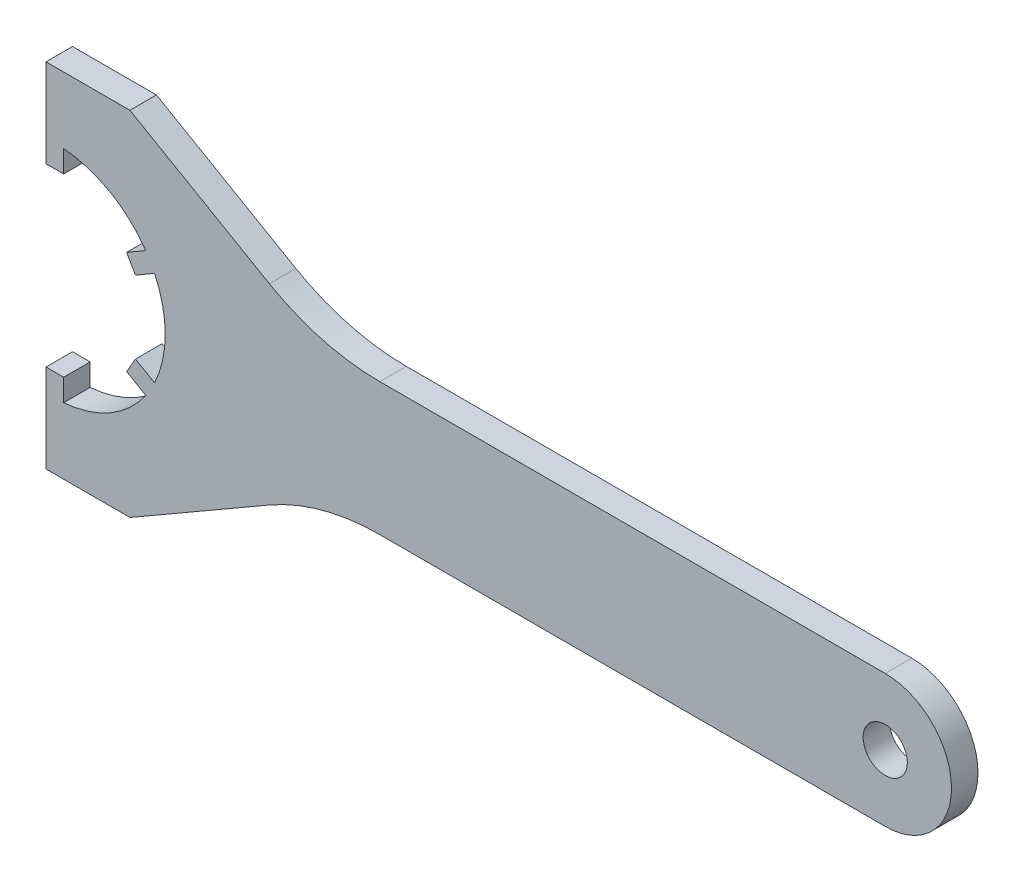
SolidWorks part; units mm, degrees
ref_plane "Front Plane" through (0, 0, 0) normal (0, 0, 1) x (1, 0, 0)
ref_plane "Top Plane" through (0, 0, 0) normal (0, 1, 0) x (1, 0, 0)
ref_plane "Right Plane" through (0, 0, 0) normal (1, 0, 0) x (0, 0, -1)
sketch "Sketch1" plane through (0, 0, 0) normal (0, 0, 1) x (1, 0, 0)
  line L0 (-31.6707, 0) -> (217.4566, 0) construction
  line L1 (2, 24.9199) -> (2, 19.9199)
  line L2 (60.1625, 15) -> (188, 15)
  line L4 (60.1625, -15) -> (188, -15)
  line L6 (16.2511, 11.692) -> (20.5812, 14.192)
  line L7 (2, 19.9199) -> (-2, 19.9199)
  line L8 (-2, 19.9199) -> (-2, 24.9199)
  line L9 (-2, 24.9199) -> (-2, 39.9199)
  line L10 (-2, 39.9199) -> (17, 39.9199)
  line L11 (17, 39.9199) -> (60.1625, 15)
  line L12 (18.2511, 8.2279) -> (16.2511, 11.692)
  line L13 (22.5812, 10.7279) -> (18.2511, 8.2279)
  line L14 (18.2511, -8.2279) -> (22.5812, -10.7279)
  line L15 (0, 42.5881) -> (0, -53.2095) construction
  line L16 (16.2511, -11.692) -> (18.2511, -8.2279)
  line L17 (20.5812, -14.192) -> (16.2511, -11.692)
  line L18 (2, -19.9199) -> (2, -24.9199)
  line L19 (-2, -19.9199) -> (2, -19.9199)
  line L20 (-2, -24.9199) -> (-2, -19.9199)
  line L27 (17, -39.9199) -> (60.1625, -15)
  line L28 (-2, -39.9199) -> (17, -39.9199)
  line L29 (-2, -24.9199) -> (-2, -39.9199)
  arc A0 (188, 15) -> (188, -15) centre (188, 0) cw
  circle A1 centre (188, 0) radius 5
  arc A2 (2, -24.9199) -> (20.5812, -14.192) centre (0, 0) ccw
  arc A3 (20.5812, 14.192) -> (2, 24.9199) centre (0, 0) ccw
  arc A4 (22.5812, -10.7279) -> (22.5812, 10.7279) centre (0, 0) ccw
  point P3 (0, 0)
  point P13 (217.4566, 0)
  point P16 (-31.6707, 0)
  point P35 (0, -19.9199)
  point P43 (0, 0)
  dimension "D1" = 50
  dimension "D10" = 10
  dimension "D2" = 2
  dimension "D3" = 4
  dimension "D4" = 5
  dimension "D5" = 15
  dimension "D6" = 19
  dimension "D7" = 150
  dimension "D8" = 15
  dimension "D9" = 190
  dimension "D11" = 39.9199
  dimension "D12" = 30
  dimension "D13" = 19.9199
  dimension "D14" = 60
  dimension "D15" = 19.9199
extrude "Boss-Extrude1" add sketch "Sketch1" along normal mid plane 6
fillet "Fillet1" radius 50 2 edges at (60.1625, 15, 0) (60.1625, -15, 0)
